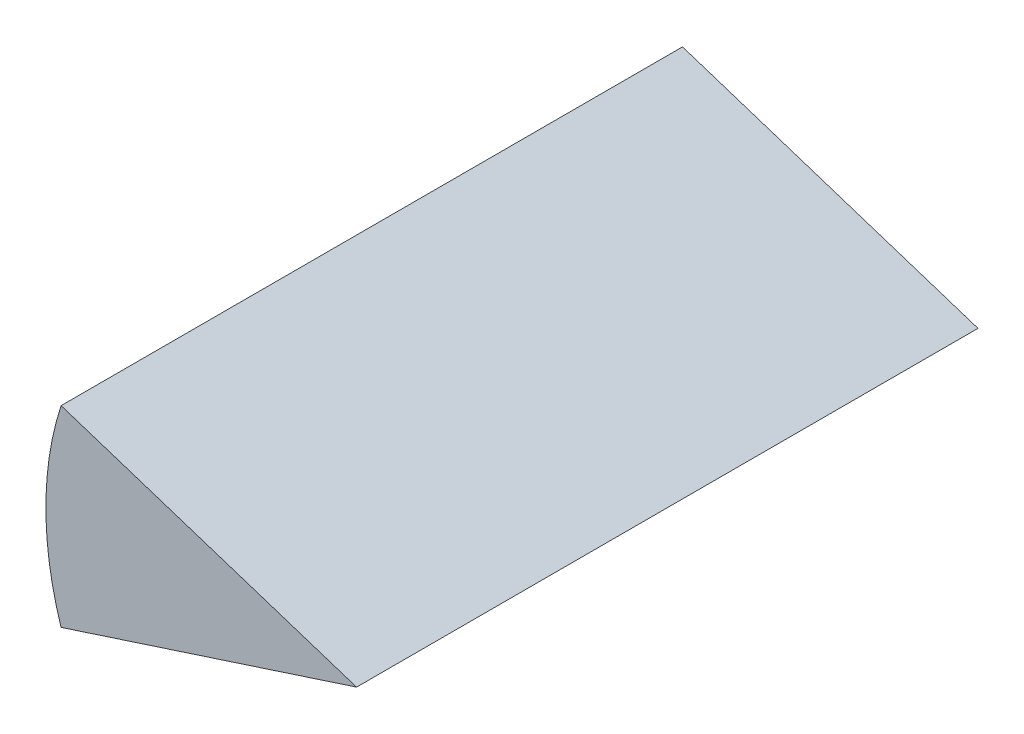
SolidWorks part; units mm, degrees
ref_plane "Alzado" through (0, 0, 0) normal (0, 0, 1) x (1, 0, 0)
ref_plane "Planta" through (0, 0, 0) normal (0, 1, 0) x (1, 0, 0)
ref_plane "Vista lateral" through (0, 0, 0) normal (1, 0, 0) x (0, 0, -1)
sketch "Croquis1" plane through (0, 0, 0) normal (0, 0, 1) x (1, 0, 0)
  line L2 (0, 0) -> (-23.7764, 7.7254)
  line L3 (0, 0) -> (-23.7764, -7.7254)
  arc A1 (-23.7764, 7.7254) -> (-23.7764, -7.7254) centre (0, 0) ccw
  dimension "D2" = 36
extrude "Saliente-Extruir1" add sketch "Croquis1" along normal blind 50
sketch "Croquis2" plane through (0, 0, 0) normal (0, 0, -1) x (-1, 0, 0)
  circle A0 centre (18.9669, 0.1029) radius 5
  dimension "D1" = 10
extrude "Cortar-Extruir1" cut sketch "Croquis2" against normal blind 10 contours A0
